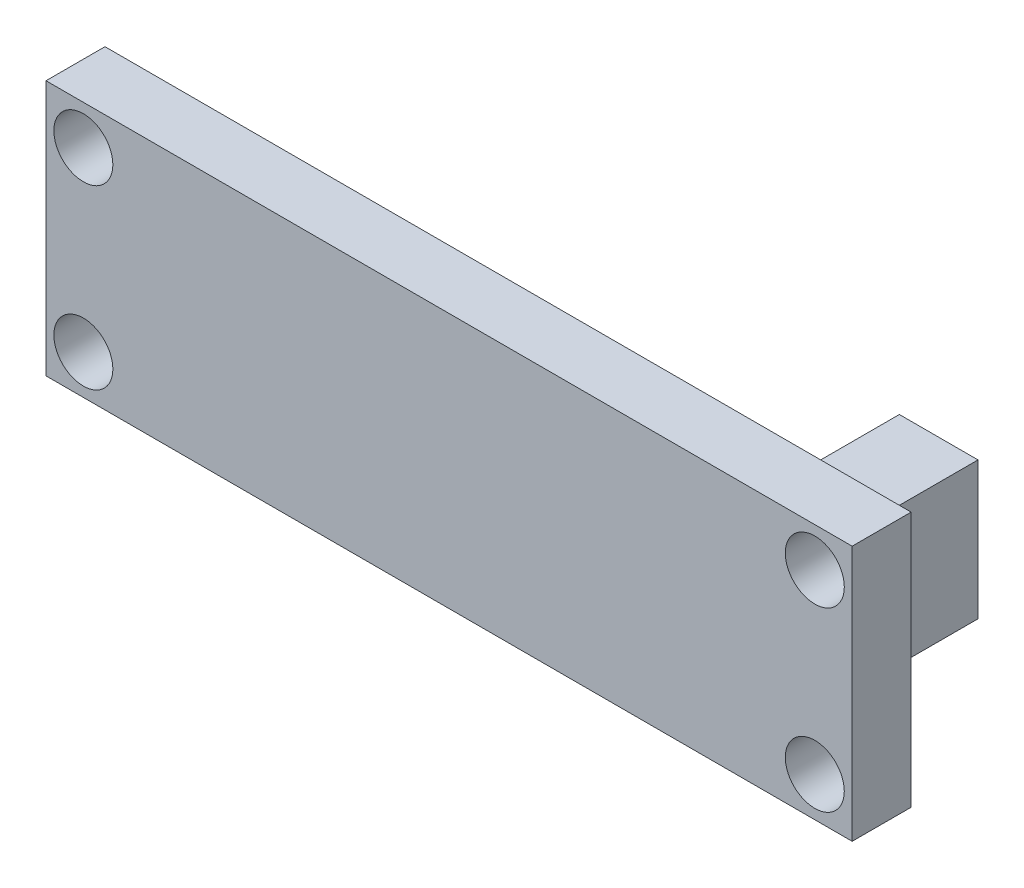
SolidWorks part; units mm, degrees
ref_plane "Alzado" through (0, 0, 0) normal (0, 0, 1) x (1, 0, 0)
ref_plane "Planta" through (0, 0, 0) normal (0, 1, 0) x (1, 0, 0)
ref_plane "Vista lateral" through (0, 0, 0) normal (1, 0, 0) x (0, 0, -1)
sketch "Croquis1" plane through (0, 0, 0) normal (0, 0, 1) x (1, 0, 0)
  line L1 (-41, 13) -> (0, 13)
  line L2 (-41, 13) -> (-41, 0)
  line L3 (-41, 0) -> (0, 0)
  line L4 (0, 13) -> (0, 0)
  dimension "D1" = 13
  dimension "D2" = 41
  dimension "D3" = 0
  dimension "D4" = 0
extrude "Saliente-Extruir1" add sketch "Croquis1" along normal blind 3
sketch "Croquis2" plane through (0, 0, 3) normal (0, 0, 1) x (1, 0, 0)
  line L0 (0, 0) -> (0, 13) construction
  line L1 (0, 13) -> (-41, 13) construction
  line L2 (-41, 0) -> (0, 0) construction
  line L3 (-41, 13) -> (-41, 0) construction
  circle A0 centre (-1.9, 11) radius 1.5
  circle A1 centre (-1.9, 2) radius 1.5
  circle A2 centre (-39.1, 11) radius 1.5
  circle A3 centre (-39.1, 2) radius 1.5
  dimension "D1" = 3
  dimension "D2" = 3
  dimension "D3" = 3
  dimension "D4" = 3
  dimension "D5" = 1.9
  dimension "D6" = 2
  dimension "D7" = 2
  dimension "D8" = 1.9
  dimension "D9" = 1.9
  dimension "D10" = 1.9
  dimension "D11" = 2
  dimension "D12" = 2
extrude "Cortar-Extruir1" cut sketch "Croquis2" against normal through all
sketch "Croquis3" plane through (0, 0, 0) normal (0, 0, -1) x (-1, 0, 0)
  line L1 (3.6, 10) -> (7.6, 10)
  line L2 (3.6, 10) -> (3.6, 3)
  line L3 (3.6, 3) -> (7.6, 3)
  line L4 (7.6, 10) -> (7.6, 3)
  circle A3 centre (1.9, 11) radius 1.5 construction
  circle A5 centre (1.9, 2) radius 1.5 construction
  dimension "D1" = 4
  dimension "D2" = 7
  dimension "D3" = 1
  dimension "D4" = 1.7
extrude "Saliente-Extruir2" add sketch "Croquis3" along normal blind 7
